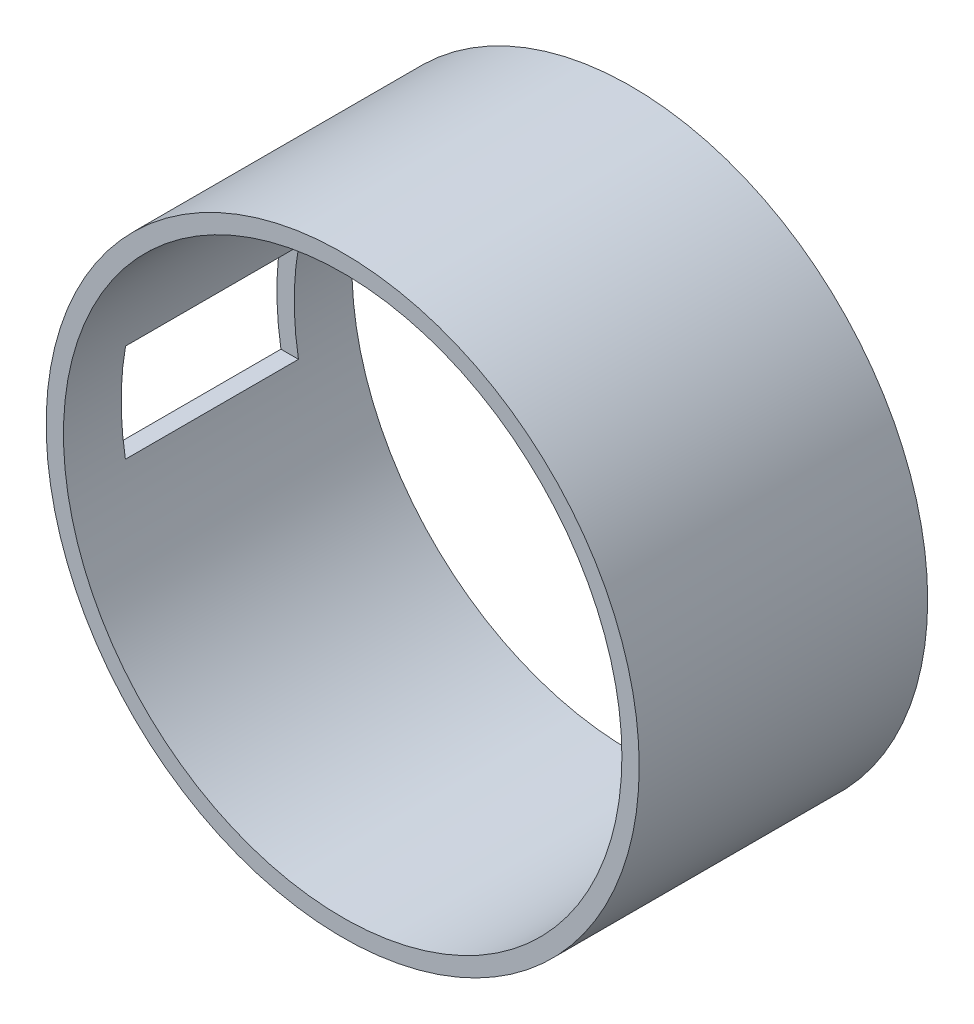
SolidWorks part; units mm, degrees
ref_plane "前视基准面" through (0, 0, 0) normal (0, 0, 1) x (1, 0, 0)
ref_plane "上视基准面" through (0, 0, 0) normal (0, 1, 0) x (1, 0, 0)
ref_plane "右视基准面" through (0, 0, 0) normal (1, 0, 0) x (0, 0, -1)
sketch "草图1" plane through (0, 0, 0) normal (0, 0, 1) x (1, 0, 0)
  circle A0 centre (0, 0) radius 9.68
  circle A1 centre (0, 0) radius 10.28
  dimension "D1" = 19.36
  dimension "D2" = 20.56
extrude "凸台-拉伸1" add sketch "草图1" along normal blind 10
sketch "草图2" plane through (0, 0, 10) normal (0, 0, 1) x (1, 0, 0)
  line L0 (-10.28, 0) -> (-9.68, 0) construction
  circle A0 centre (0, 0) radius 10.28 construction
  circle A1 centre (0, 0) radius 9.68 construction
ref_plane "基准面1" through (-10.28, 0, 0) normal (-1, 0, 0) x (0, 0, 1)
sketch "草图3" plane through (-10.28, 0, 0) normal (-1, 0, 0) x (0, 0, 1)
  line L0 (0, 0) -> (2, 0) construction
  line L1 (2, 0) -> (2, 1.7148) construction
  line L3 (2, 1.7148) -> (8, 1.7148)
  line L4 (2, 1.7148) -> (2, -1.6852)
  line L5 (2, -1.6852) -> (8, -1.6852)
  line L6 (8, 1.7148) -> (8, -1.6852)
  dimension "D1" = 6
  dimension "D2" = 3.4
extrude "切除-拉伸1" cut sketch "草图3" against normal blind 1.5
